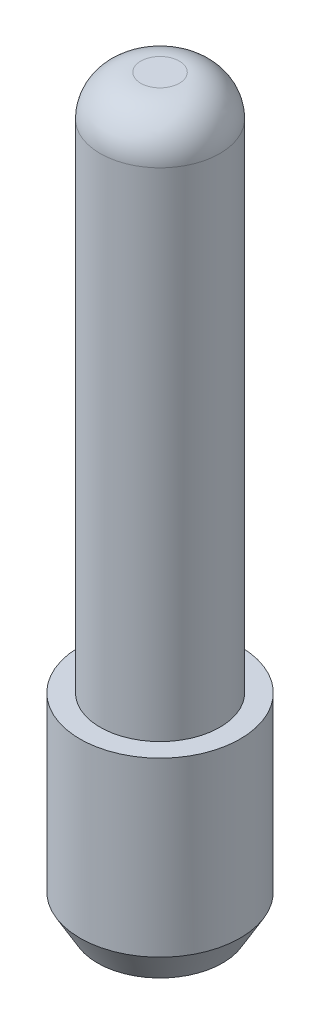
SolidWorks part; units mm, degrees
material "PVC Rigid"
ref_plane "Front Plane" through (0, 0, 0) normal (0, 0, 1) x (1, 0, 0)
ref_plane "Top Plane" through (0, 0, 0) normal (0, 1, 0) x (1, 0, 0)
ref_plane "Right Plane" through (0, 0, 0) normal (1, 0, 0) x (0, 0, -1)
sketch "Sketch4" plane through (0, 0, 0) normal (0, 0, 1) x (1, 0, 0)
  line L0 (0, 0) -> (0, 628.1483) construction
  line L1 (0, 0) -> (3.95, 0)
  line L2 (3.95, 0) -> (3.95, 10)
  line L3 (3.95, 10) -> (2.95, 10)
  line L4 (2.95, 10) -> (2.95, 36.5)
  line L5 (2.95, 36.5) -> (0, 36.5)
  line L6 (0, 0) -> (0, 36.5)
  dimension "D1" = 3.95
  dimension "D2" = 2.95
  dimension "D3" = 36.5
  dimension "D4" = 10
revolve "Revolve1" add sketch "Sketch4" angle 360 about L0
fillet "Fillet1" radius 2 1 edges at (0, 36.5, -2.95)
chamfer "Chamfer2" distance 1.5 angle 30 1 edges at (0, 0, -3.95)
